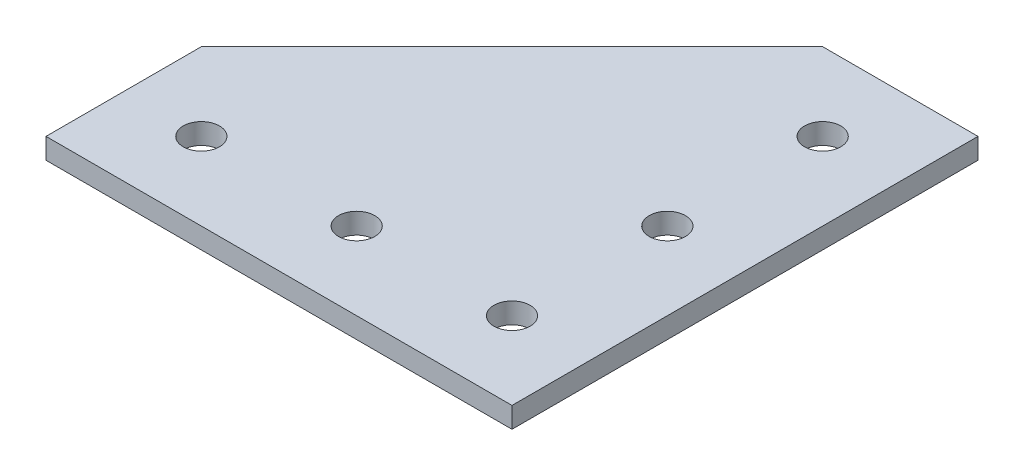
SolidWorks part; units mm, degrees
material "6061-T6 (SS)"
ref_plane "Front Plane" through (0, 0, 0) normal (0, 0, 1) x (1, 0, 0)
ref_plane "Top Plane" through (0, 0, 0) normal (0, 1, 0) x (1, 0, 0)
ref_plane "Right Plane" through (0, 0, 0) normal (1, 0, 0) x (0, 0, -1)
sketch "Sketch1" plane through (0, 0, 0) normal (0, 1, 0) x (1, 0, 0)
  line L1 (0, 0) -> (-90, 0)
  line L2 (0, 0) -> (0, 90)
  line L4 (-90, 0) -> (-90, 30)
  line L7 (-90, 30) -> (-30, 90)
  line L8 (-30, 90) -> (0, 90)
  dimension "D1" = 30
  dimension "D5" = 90
extrude "Boss-Extrude1" add sketch "Sketch1" along normal blind 4
hole_wizard "M6 Clearance Hole1" positions "Sketch2" profile "Sketch3" hole size "M6" standard "DIN" end condition through all
sketch "Sketch2" plane through (0, 4, 0) normal (0, 1, 0) x (1, 0, 0)
  line L0 (-75, 15) -> (-45, 15) construction
  line L1 (-45, 15) -> (-15, 15) construction
  line L2 (-15, 15) -> (-15, 45) construction
  line L3 (-15, 45) -> (-15, 75) construction
  line L6 (-15, 75) -> (-15, 90) construction
  line L7 (0, 90) -> (-30, 90) construction
  line L9 (-75, 15) -> (-90, 15) construction
  line L10 (-90, 30) -> (-90, 0) construction
  point P0 (-75, 15)
  point P2 (-45, 15)
  point P4 (-15, 15)
  point P6 (-15, 45)
  point P8 (-15, 75)
  dimension "D1" = 15
sketch "Sketch3" plane through (-75, 4, -15) normal (1, 0, 0) x (0, 0, 1)
  line L0 (0, 0) -> (0, 4)
  line L1 (0, 4) -> (3.5, 4)
  line L2 (3.5, 4) -> (3.5, 0)
  line L5 (3.5, 0) -> (0, 0)
  line L11 (0, -6.35) -> (0, 107.95) construction
  dimension "Thru Hole Dia." = 7
  dimension "Thru Hole Depth" = 4
